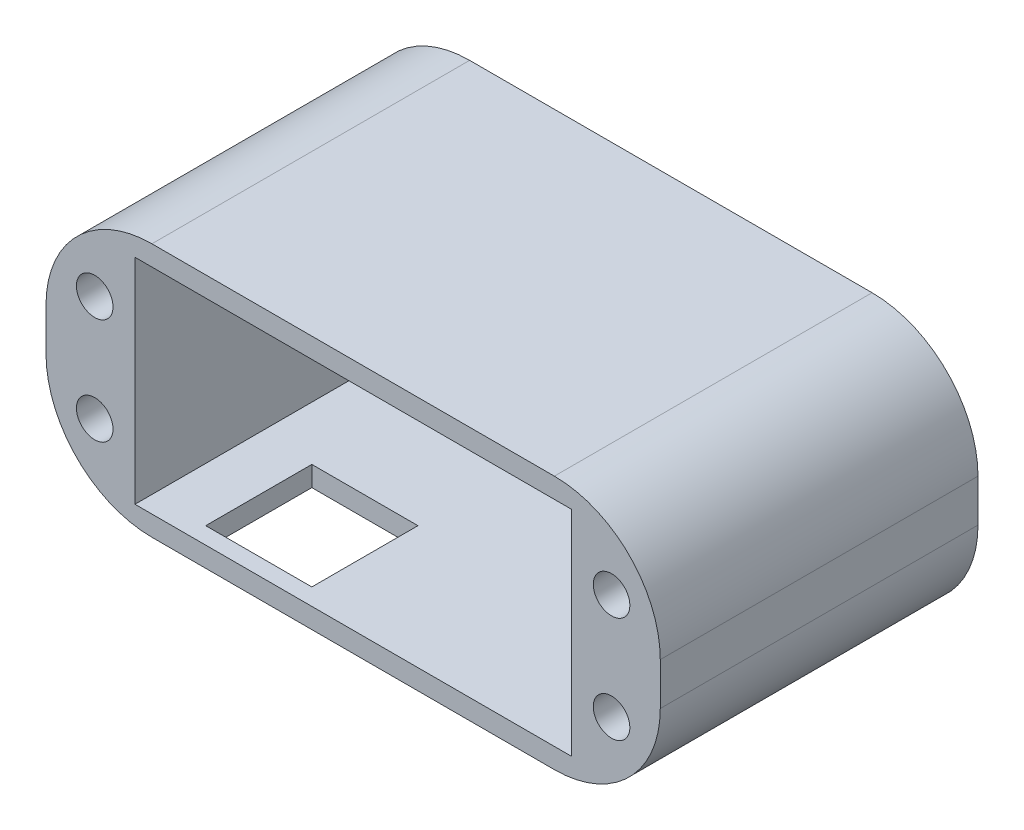
SolidWorks part; units mm, degrees
ref_plane "Front Plane" through (0, 0, 0) normal (0, 0, 1) x (1, 0, 0)
ref_plane "Top Plane" through (0, 0, 0) normal (0, 1, 0) x (1, 0, 0)
ref_plane "Right Plane" through (0, 0, 0) normal (1, 0, 0) x (0, 0, -1)
sketch "Sketch1" plane through (0, 0, 0) normal (0, 0, 1) x (1, 0, 0)
  line L1 (29, -12) -> (-29, -12)
  line L2 (29, -12) -> (29, 12)
  line L3 (29, 12) -> (-29, 12)
  line L4 (-29, -12) -> (-29, 12)
  line L5 (29, -12) -> (-29, 12) construction
  line L6 (29, 12) -> (-29, -12) construction
  point P0 (0, 0)
  dimension "D1" = 58
  dimension "D2" = 24
extrude "Boss-Extrude1" add sketch "Sketch1" against normal blind 30
sketch "Sketch8" plane through (0, 0, 0) normal (0, 0, 1) x (1, 0, 0)
  circle A0 centre (-24.4, 5) radius 1
  circle A1 centre (-24.4, -5) radius 1
  circle A2 centre (24.4, -5) radius 1
  circle A3 centre (24.4, 5) radius 1
  dimension "D1" = 2
  dimension "D2" = 2
  dimension "D3" = 2
  dimension "D4" = 2
hole_wizard "#8-32 Tapped Hole2" positions "3DSketch5" profile "Sketch11" tap size "#8-32" standard "ANSI Inch"
sketch3d "3DSketch5"
  point P0 (24.4, -5, 0)
  point P3 (24.4, 5, 0)
  point P6 (-24.4, -5, 0)
  point P9 (-24.4, 5, 0)
sketch "Sketch11" plane through (24.4, -5, 0) normal (1, 0, 0) x (0, -1, 0)
  line L0 (0, 0) -> (0, 13.0378)
  line L1 (0, 13.0378) -> (1.7272, 12)
  line L2 (1.7272, 12) -> (1.7272, 0)
  line L5 (1.7272, 0) -> (0, 0)
  line L10 (0, 13.0378) -> (-1.7272, 12) construction
  line L11 (0, -6.35) -> (0, 107.95) construction
  dimension "Tap Drill Dia." = 3.4544
  dimension "Tap Drill Depth" = 12
  dimension "Drill Angle" = 118
cosmetic thread "Hole Thread38" parameters "D1"=2.075, "D2"=4.1656
cosmetic thread "Hole Thread39" parameters "D1"=2.075, "D2"=4.1656
cosmetic thread "Hole Thread40" parameters "D1"=2.075, "D2"=4.1656
cosmetic thread "Hole Thread41" parameters "D1"=2.075, "D2"=4.1656
sketch "Sketch18" plane through (0, 0, 0) normal (0, 0, 1) x (1, 0, 0)
  line L1 (20.6, 10.1) -> (-20.6, 10.1)
  line L2 (20.6, 10.1) -> (20.6, -10.1)
  line L3 (20.6, -10.1) -> (-20.6, -10.1)
  line L4 (-20.6, 10.1) -> (-20.6, -10.1)
  line L5 (20.6, 10.1) -> (-20.6, -10.1) construction
  line L6 (20.6, -10.1) -> (-20.6, 10.1) construction
  point P0 (0, 0)
  dimension "D1" = 41.2
  dimension "D2" = 20.2
extrude "Cut-Extrude6" cut sketch "Sketch18" against normal blind 28
sketch "Sketch22" plane through (0, 0, -30) normal (0, 0, -1) x (-1, 0, 0)
  circle A0 centre (10.5, 0) radius 1.505
  dimension "D1" = 3.01
extrude "Cut-Extrude9" cut sketch "Sketch22" against normal blind 2
sketch "Sketch24" plane through (0, -10.1, 0) normal (0, 1, 0) x (1, 0, 0)
  line L1 (-15.51, 1.59) -> (-5.49, 1.59)
  line L2 (-15.51, 1.59) -> (-15.51, 11.61)
  line L3 (-15.51, 11.61) -> (-5.49, 11.61)
  line L4 (-5.49, 1.59) -> (-5.49, 11.61)
  line L5 (-15.51, 1.59) -> (-5.49, 11.61) construction
  line L6 (-15.51, 11.61) -> (-5.49, 1.59) construction
  point P0 (-10.5, 6.6)
  dimension "D1" = 10.02
  dimension "D2" = 10.02
extrude "Cut-Extrude11" cut sketch "Sketch24" against normal blind 2
fillet "Fillet1" radius 10 1 edges at (-29, 12, -15)
fillet "Fillet2" radius 10 1 edges at (29, 12, -15)
fillet "Fillet3" radius 10 1 edges at (29, -12, -15)
fillet "Fillet4" radius 10 1 edges at (-29, -12, -15)
